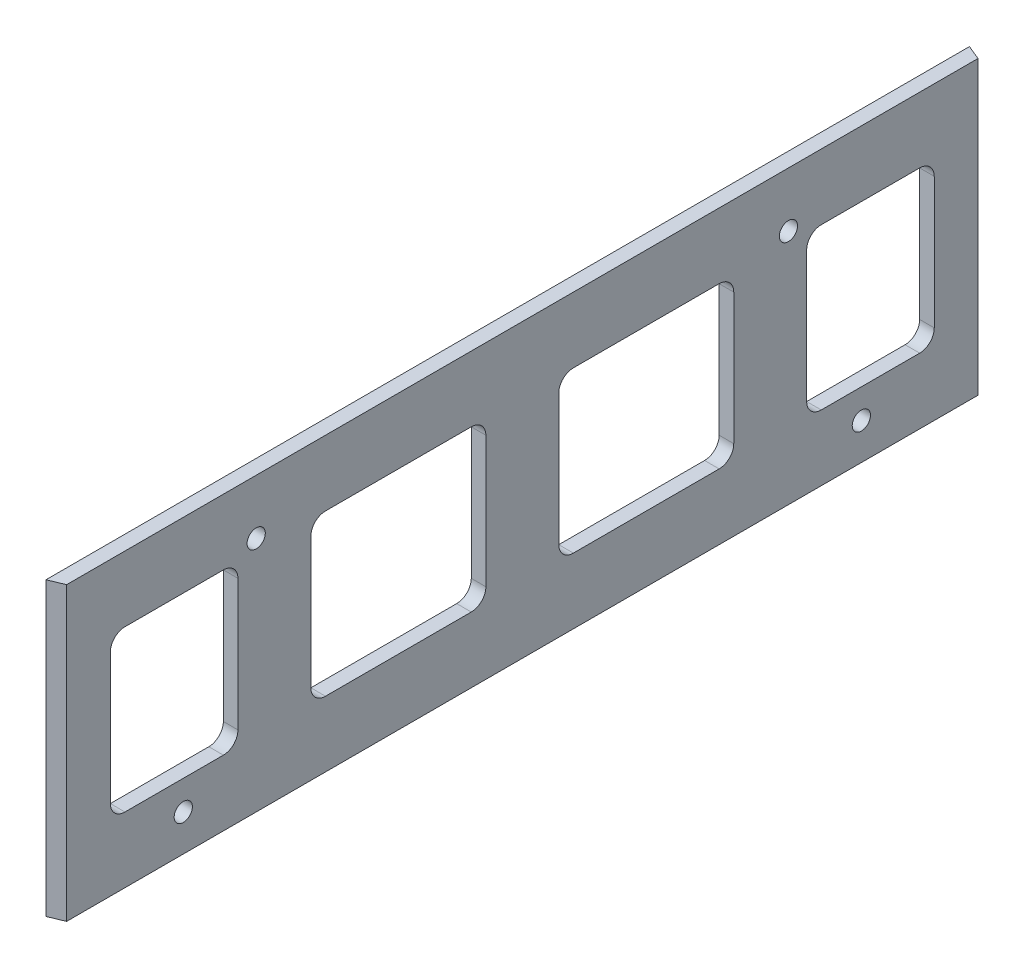
SolidWorks part; units mm, degrees
material "6061 合金"
ref_plane "前视基准面" through (0, 0, 0) normal (0, 0, 1) x (1, 0, 0)
ref_plane "上视基准面" through (0, 0, 0) normal (0, 1, 0) x (1, 0, 0)
ref_plane "右视基准面" through (0, 0, 0) normal (1, 0, 0) x (0, 0, -1)
sketch "草图1" plane through (0, 0, 0) normal (0, 0, 1) x (1, 0, 0)
  line L1 (0, 55) -> (-4, 55)
  line L2 (0, 55) -> (0, -25)
  line L3 (0, -25) -> (-4, -25)
  line L4 (-4, 55) -> (-4, -25)
  line L6 (25, 20) -> (-22.1957, 20) construction
  dimension "D1" = 4
extrude "拉伸3" add sketch "草图1" against normal blind 250
sketch "草图4" plane through (0, -25, 0) normal (0, -1, 0) x (1, 0, 0)
  line L0 (-4, 0) -> (-4, 1.6569)
  line L1 (-4, 1.6569) -> (0, 0)
  line L2 (-4, 0) -> (0, 0) construction
  line L3 (-4, 0) -> (0, 0)
  dimension "D1" = 22.5
extrude "拉伸4" add sketch "草图4" against normal up to surface (80 mm away) up to face at (-2, 55, -125)
sketch "草图6" plane through (0, -25, 0) normal (0, -1, 0) x (1, 0, 0)
  line L0 (-4, -250) -> (-4, -251.6569)
  line L1 (-4, -251.6569) -> (0, -250)
  line L2 (0, -250) -> (-4, -250)
  dimension "D1" = 22.5
extrude "拉伸5" add sketch "草图6" against normal up to surface (80 mm away) up to face at (-2, 55, -124.5858)
ref_plane "基准面2" through (0, 55, 0) normal (0, 1, 0) x (-1, 0, 0)
sketch "草图8" plane through (0, 0, 0) normal (1, 0, 0) x (0, 0, -1)
  line L0 (125, 55) -> (125, -46.0925) construction
  line L1 (12, 37) -> (47, 37)
  line L2 (12, 37) -> (12, -7)
  line L3 (12, -7) -> (47, -7)
  line L4 (47, 37) -> (47, -7)
  line L5 (67, 37) -> (115, 37)
  line L6 (67, 37) -> (67, -7)
  line L7 (67, -7) -> (115, -7)
  line L8 (115, 37) -> (115, -7)
  line L9 (135, 37) -> (183, 37)
  line L10 (135, 37) -> (135, -7)
  line L11 (135, -7) -> (183, -7)
  line L12 (183, 37) -> (183, -7)
  line L13 (203, 37) -> (238, 37)
  line L14 (203, 37) -> (203, -7)
  line L15 (203, -7) -> (238, -7)
  line L16 (238, 37) -> (238, -7)
  line L17 (250, 55) -> (0, 55) construction
  line L18 (3.3431, 15) -> (268.2202, 15) construction
  line L19 (3.3431, 50) -> (3.3431, -20) construction
  line L20 (0, 2.2) -> (0, -2.2) construction
  dimension "D1" = 44
  dimension "D2" = 35
  dimension "D3" = 48
  dimension "D4" = 20
  dimension "D5" = 12
extrude "切除-拉伸1" cut sketch "草图8" against normal through all
sketch "草图2" plane through (-4, 0, 0) normal (-1, 0, 0) x (0, 0, 1)
  line L0 (-125, 55) -> (-125, -58.5354) construction
  line L1 (-251.6569, 55) -> (1.6569, 55) construction
  line L2 (-251.6569, -25) -> (1.6569, -25) construction
  circle A0 centre (-198, 40) radius 2.5
  circle A1 centre (-218, -15) radius 2.5
  circle A2 centre (-52, 40) radius 2.5
  circle A3 centre (-32, -15) radius 2.5
  dimension "D5" = 5
  dimension "D1" = 146
  dimension "D2" = 186
  dimension "D3" = 10
  dimension "D4" = 15
extrude "切除-拉伸2" cut sketch "草图2" against normal through all
fillet "圆角1" radius 4 4 edges at (-2, -7, -47) (-2, -7, -12) (-2, 37, -47) (-2, 37, -12)
fillet "圆角2" radius 4 4 edges at (-2, -7, -115) (-2, -7, -67) (-2, 37, -115) (-2, 37, -67)
fillet "圆角3" radius 4 4 edges at (-2, -7, -135) (-2, 37, -135) (-2, 37, -183) (-2, -7, -183)
fillet "圆角4" radius 4 4 edges at (-2, 37, -203) (-2, -7, -203) (-2, -7, -238) (-2, 37, -238)
